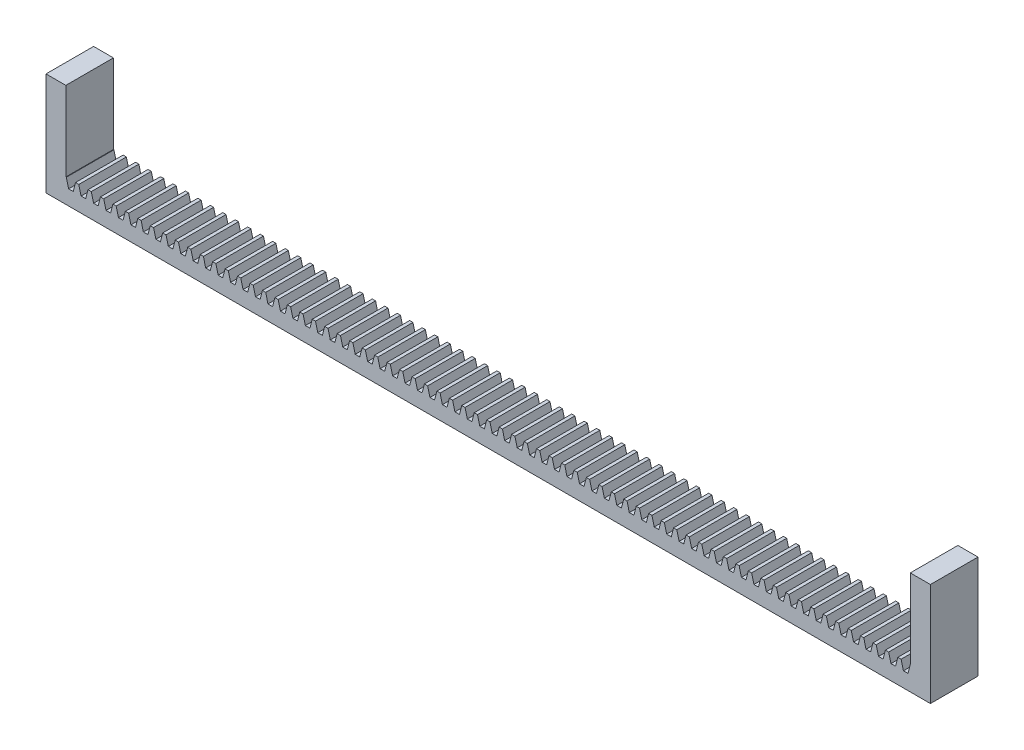
SolidWorks part; units mm, degrees
extrude "Blank" add sketch "BlankSke" against normal blind 12
sketch "BlankSke" plane through (0, 0, 0) normal (0, 0, 1) x (1, 0, 0)
  line L1 (0, 0) -> (223, 0)
  line L2 (0, 0) -> (0, 6)
  line L3 (0, 6) -> (223, 6)
  line L4 (223, 0) -> (223, 6)
  dimension "Length" = 223
  dimension "Blank_height" = 6
ref_plane "Plane1" through (0, 0, 0) normal (0, 0, 1) x (1, 0, 0)
ref_plane "Plane2" through (0, 0, 0) normal (0, 1, 0) x (1, 0, 0)
ref_plane "Plane3" through (0, 0, 0) normal (1, 0, 0) x (0, 0, -1)
sketch "HoldingSke" plane through (0, 0, 0) normal (0, 1, 0) x (1, 0, 0)
  line L0 (0, 0) -> (0.1392, 0.9903)
  line L1 (-15, 0) -> (100, 0) construction
  line L2 (0, 0) -> (-2.1039, 2.3779)
  line L3 (0, 0) -> (-11.863, 4.5341)
  line L4 (0, 0) -> (4.8292, 7.1596)
  line L5 (0, 0) -> (-23.7986, -8.8762)
  line L6 (0, 0) -> (-10.5278, -7.1032)
  line L9 (-67.7845, 28.3722) -> (98.7369, 71.4376)
  line L10 (-76.2, 3.3779) -> (-71.2, 3.3779)
  line L11 (0, 0) -> (-12, 0)
  line L12 (-76.2, 101.6) -> (-76.162, 101.6)
  line L13 (24.9733, 27.94) -> (52.9518, 28.4284)
  line L14 (24.9733, 27.94) -> (24.9743, 27.94)
  line L15 (24.9733, 27.94) -> (100.4006, 29.5858)
  circle A0 centre (0, 0) radius 19.05
  circle A1 centre (0, 0) radius 2.5
  circle A2 centre (0, 0) radius 12.7
  dimension "MPH" = 5
  dimension "Diameter" = 38.1
  dimension "Num_teeth" = 56
  dimension "Pitch" = 1
  dimension "Show_teeth" = 998
  dimension "Thickness" = 12.7
  dimension "Ap" = 14.5
  dimension "Pitch_height" = 5
  dimension "Width" = 12
  dimension "Backlash" = 0.038
  dimension "Addendum_fac" = 1
  dimension "Dedendum_fac" = 1.25
  dimension "Clearance_fac" = 0.25
  dimension "Dedendum_add" = 0.001
  dimension "Length" = 172
  dimension "Module" = 1
sketch "TooCutSkeIll" plane through (0, 0, 0) normal (0, 0, 1) x (1, 0, 0)
  line L0 (-1.1503, 5.97) -> (-0.6248, 3.9382)
  line L1 (-0.3818, 3.75) -> (0.3818, 3.75)
  line L2 (0.6248, 3.9382) -> (1.1503, 5.97)
  line L3 (223, 6) -> (0, 6) construction
  line L4 (0, 0) -> (0, 64.897) construction
  line L5 (-13.208, 5) -> (12.954, 5) construction
  line L6 (0, 0) -> (223, 0) construction
  line L7 (0.8994, 5) -> (0.8994, 48.7463) construction
  line L8 (-0.8994, 5) -> (-0.8994, 48.7463) construction
  line L9 (1.189, 6) -> (1.189, 6.0254)
  line L10 (-1.189, 6) -> (-1.189, 6.0254)
  line L11 (-1.189, 6.0254) -> (1.189, 6.0254)
  arc A0 (0.3818, 3.75) -> (0.6248, 3.9382) centre (0.3818, 4.001) ccw
  arc A1 (-0.6248, 3.9382) -> (-0.3818, 3.75) centre (-0.3818, 4.001) ccw
  arc A2 (1.189, 6) -> (1.1503, 5.97) centre (1.189, 5.96) ccw
  arc A3 (-1.1503, 5.97) -> (-1.189, 6) centre (-1.189, 5.96) ccw
  dimension "Pitch_height" = 5
  dimension "Addendum_plus" = 1.0254
  dimension "Pressure_angle" = 14.5
  dimension "Gap_width" = 1.7988
  dimension "Dedendum" = 1.25
extrude "ToothCutIll" [suppressed] cut sketch "TooCutSkeIll" against normal through all
sketch "TooCutSkeSim" plane through (0, 0, 0) normal (0, 0, 1) x (1, 0, 0)
  line L0 (0.5761, 3.75) -> (-0.5761, 3.75)
  line L1 (1.1646, 6.0254) -> (0.5761, 3.75)
  line L2 (0, 17.4625) -> (0, 53.467) construction
  line L3 (1.1646, 6.0254) -> (-1.1646, 6.0254)
  line L6 (-1.1646, 6.0254) -> (-0.5761, 3.75)
  line L9 (-0.8994, 5) -> (0.8994, 5) construction
  line L10 (0, 0) -> (223, 0) construction
  line L11 (0.8994, 5) -> (0.8994, 53.467) construction
  line L12 (-0.8994, 5) -> (-0.8994, 53.467) construction
  dimension "Pitch_height" = 5
  dimension "Addendum_plus" = 1.0254
  dimension "Pressure_angle" = 14.5
  dimension "Gap_width" = 1.7988
  dimension "Dedendum" = 1.25
extrude "ToothCutSim" cut sketch "TooCutSkeSim" against normal through all
pattern_linear "TeethCuts" count 71 spacing 3.1416 along (1, 0, 0) of "ToothCutSim"
sketch "Sketch1" plane through (0, 0, 0) normal (0, -1, 0) x (1, 0, 0)
  line L5 (0, 0) -> (0, -12)
  line L10 (0, 0) -> (5, 0)
  line L12 (223, 0) -> (217.9279, 0)
  line L13 (0, 0) -> (223, 0) construction
  line L15 (217.9279, -12) -> (223, -12)
  line L16 (223, -12) -> (223, 0)
  line L18 (217.9279, 0) -> (217.9279, -12)
  line L19 (5, 0) -> (5, -12)
  line L20 (0, -12) -> (223, -12) construction
  line L21 (5, -12) -> (0, -12)
extrude "Boss-Extrude1" add sketch "Sketch1" against normal blind 26
equation "' \"Module@HoldingSke\" = 6.35"
equation "' \"Num_teeth@HoldingSke\" = 12"
equation "' \"Ap@HoldingSke\" =  20"
equation "' \"Ap@HoldingSke\" = 20"
equation "' \"Width@HoldingSke\" = 0.25 * 25.4"
equation "' \"Show_teeth@HoldingSke\" = 500"
equation "' \"Backlash@HoldingSke\" = 0.009 * 25.4"
equation "' \"Addendum_fac@HoldingSke\" = 1.0"
equation "' \"Dedendum_fac@HoldingSke\" = 1.25"
equation "' \"Dedendum_add@HoldingSke\" = 0.00005 * 25.4"
equation "' \"Clearance_fac@HoldingSke\" = 0.25"
equation "' \"Pitch_height@HoldingSke\" = 1 * 25.4"
equation "' \"Length@HoldingSke\" = 4.71 * 25.4"
equation "\"Pitch@HoldingSke\" = 1 / \"Module@HoldingSke\""
equation "\"MPH@HoldingSke\" = \"Dedendum_fac@HoldingSke\" / \"Pitch@HoldingSke\" + 2 * \"Dedendum_add@HoldingSke\" + 0.002 * 25.4"
equation "\"MPH@HoldingSke\" = ((sgn( \"MPH@HoldingSke\" - \"Pitch_height@HoldingSke\")+1)*( \"MPH@HoldingSke\" - \"Pitch_height@HoldingSke\"))/2 + \"Pitch_height@HoldingSke\""
equation "\"Blank_height@BlankSke\" = \"Pitch_height@HoldingSke\" + \"Addendum_fac@HoldingSke\"  / \"Pitch@HoldingSke\" "
equation "\"Face_width@Blank\" = \"Width@HoldingSke\""
equation "\"Pressure_angle@TooCutSkeIll\" = \"Ap@HoldingSke\""
equation "\"Addendum_plus@TooCutSkeIll\" =  \"Addendum_fac@HoldingSke\"  / \"Pitch@HoldingSke\" + 0.001 *25.4"
equation "\"Dedendum@TooCutSkeIll\" = \"Dedendum_fac@HoldingSke\"  / \"Pitch@HoldingSke\""
equation "\"Pitch_height@TooCutSkeIll\" =  \"MPH@HoldingSke\""
equation "\"Gap_width@TooCutSkeIll\" = 3.14159265 / 2 / \"Pitch@HoldingSke\" + 6 * \"Backlash@HoldingSke\""
equation "\"Pressure_angle@TooCutSkeSim\" = \"Ap@HoldingSke\""
equation "\"Addendum_plus@TooCutSkeSim\" =  \"Addendum_fac@HoldingSke\"  / \"Pitch@HoldingSke\" + 0.001 * 25.4"
equation "\"Dedendum@TooCutSkeSim\" = \"Dedendum_fac@HoldingSke\"  / \"Pitch@HoldingSke\""
equation "\"Pitch_height@TooCutSkeSim\" =  \"MPH@HoldingSke\""
equation "\"Gap_width@TooCutSkeSim\" = 3.14159265 / 2 / \"Pitch@HoldingSke\" + 6 * \"Backlash@HoldingSke\""
equation "\"Root_fillet@TooCutSkeIll\" = \"Clearance_fac@HoldingSke\" / \"Pitch@HoldingSke\" + \"Dedendum_add@HoldingSke\""
equation "\"Break_rad@TooCutSkeIll\" = 0.02 / \"Pitch@HoldingSke\" * 2"
equation "\"Linear_pitch@TeethCuts\" = 3.14159265 / \"Pitch@HoldingSke\""
equation "\"Num_teeth@HoldingSke\" = int( ( \"Length@HoldingSke\" + 0 ) / (3.14159265 / \"Pitch@HoldingSke\")) + 0.9999  + 1"
equation " \"Num_teeth@TeethCuts\" = int( \"Show_teeth@HoldingSke\" ) + 1"
equation " \"Num_teeth@TeethCuts\" = ((sgn( \"Num_teeth@TeethCuts\" - \"Num_teeth@HoldingSke\" )-1)*( \"Num_teeth@TeethCuts\" - \"Num_teeth@HoldingSke\" ))/-2+ \"Num_teeth@HoldingSke\""
equation " \"Num_teeth@TeethCuts\" = ((sgn( \"Num_teeth@TeethCuts\" - 2.0)+1)*( \"Num_teeth@TeethCuts\" - 2.0))/2 +2.0"
